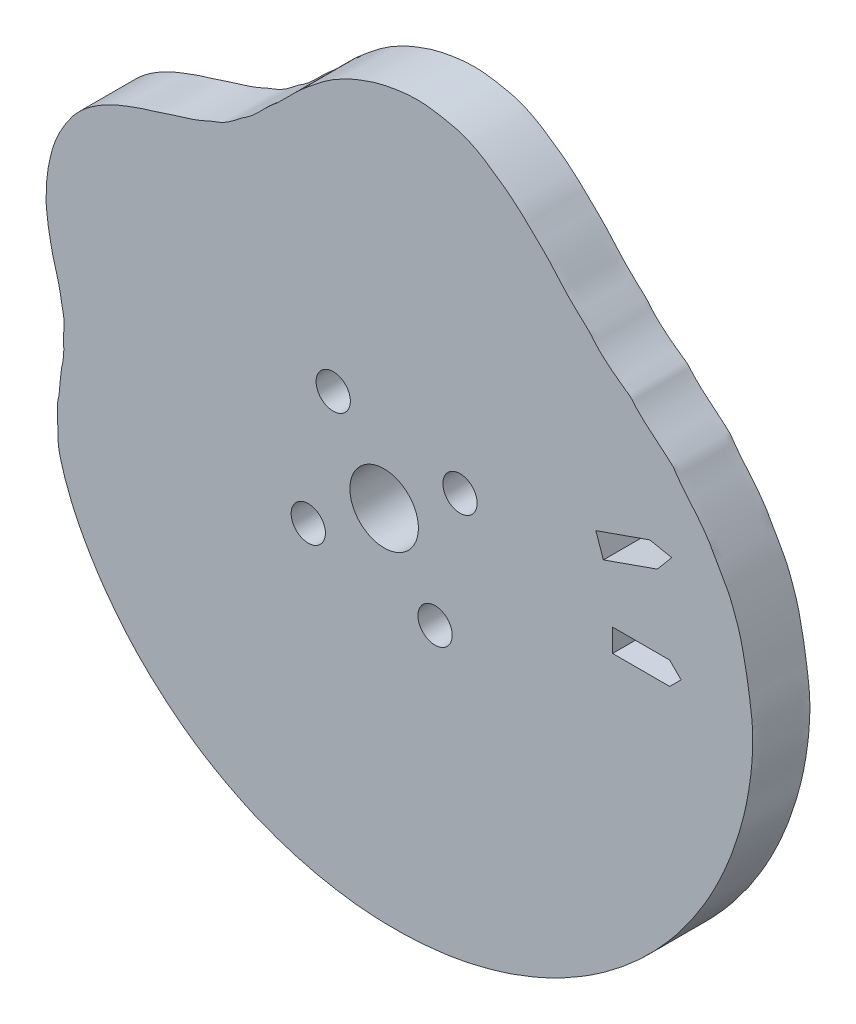
SolidWorks part; units mm, degrees
ref_plane "前视基准面" through (0, 0, 0) normal (0, 0, 1) x (1, 0, 0)
ref_plane "上视基准面" through (0, 0, 0) normal (0, 1, 0) x (1, 0, 0)
ref_plane "右视基准面" through (0, 0, 0) normal (1, 0, 0) x (0, 0, -1)
other "Configuration Table"
curve "曲线1"
sketch "草图2" plane through (0, 0, 0) normal (0, 0, 1) x (1, 0, 0)
  spline S0 degree 3 number of poles 1882 (32.21, 0) -> (32.21, 0) construction
  spline S1 degree 3 number of poles 1882 (32.21, 0) -> (32.21, 0)
extrude "凸台-拉伸1" add sketch "草图2" along normal blind 5
sketch "草图3" plane through (0, 0, 5) normal (0, 0, 1) x (1, 0, 0)
  line L0 (0, 0) -> (36.7853, 0) construction
  line L1 (20, 1) -> (20, -1)
  line L2 (20, -1) -> (25, -1)
  line L3 (25, -1) -> (26, 0)
  line L4 (26, 0) -> (25, 1)
  line L5 (25, 1) -> (20, 1)
  dimension "D1" = 2
  dimension "D2" = 5
  dimension "D3" = 5
  dimension "D4" = 20
extrude "切除-拉伸1" cut sketch "草图3" against normal blind 5
sketch "草图5" plane through (0, 0, 5) normal (0, 0, 1) x (1, 0, 0)
  circle A0 centre (0, 0) radius 3
  dimension "D1" = 6
extrude "切除-拉伸2" cut sketch "草图5" against normal blind 5
sketch "草图6" plane through (0, 0, 5) normal (0, 0, 1) x (1, 0, 0)
  circle A0 centre (-63.5031, 118.7177) radius 1.5
  circle A1 centre (-56.1434, 117.7926) radius 1.5
  circle A2 centre (-64.7361, 117.0003) radius 1.5
  circle A3 centre (-72.0958, 117.9254) radius 1.5
  dimension "D1" = 3
  dimension "D2" = 3
  dimension "D3" = 3
  dimension "D4" = 3
sketch "草图7" plane through (0, 0, 5) normal (0, 0, 1) x (1, 0, 0)
  line L6 (18.5349, 7.58) -> (19.1986, 5.6934)
  line L7 (18.5349, 7.58) -> (23.2516, 9.2392)
  line L8 (23.2516, 9.2392) -> (25.1824, 8.8583)
  line L9 (25.1824, 8.8583) -> (23.9153, 7.3525)
  line L10 (23.9153, 7.3525) -> (19.1986, 5.6934)
  dimension "D2" = 5
  dimension "D3" = 2
  dimension "D4" = 5
extrude "切除-拉伸4" cut sketch "草图7" against normal blind 10
sketch "草图8" plane through (0, 0, 5) normal (0, 0, 1) x (1, 0, 0)
  circle A0 centre (-4.4579, 6.6428) radius 1.5
  circle A1 centre (-6.6428, -4.4579) radius 1.5
  circle A2 centre (6.6428, 4.4579) radius 1.5
  circle A3 centre (4.4579, -6.6428) radius 1.5
extrude "切除-拉伸5" cut sketch "草图8" against normal blind 10
